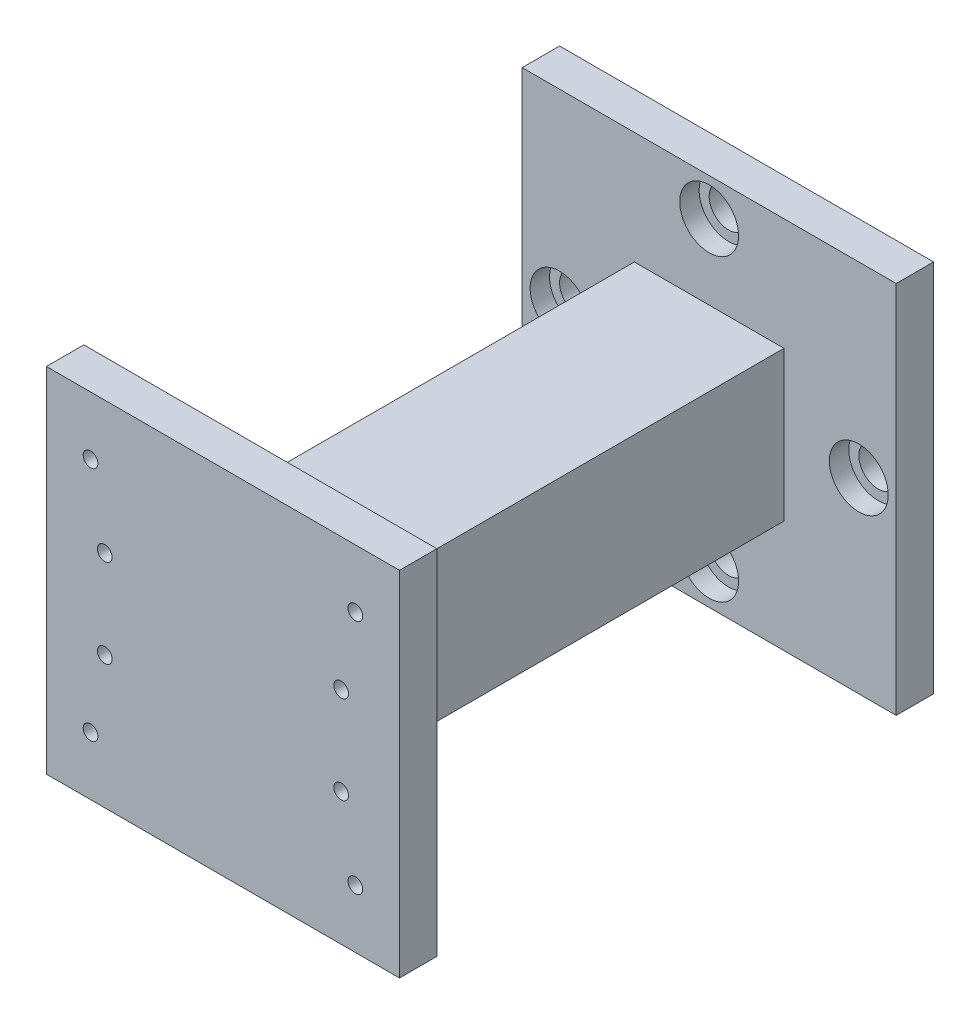
SolidWorks part; units mm, degrees
ref_plane "Front Plane" through (0, 0, 0) normal (0, 0, 1) x (1, 0, 0)
ref_plane "Top Plane" through (0, 0, 0) normal (0, 1, 0) x (1, 0, 0)
ref_plane "Right Plane" through (0, 0, 0) normal (1, 0, 0) x (0, 0, -1)
sketch "Sketch2" plane through (0, 0, 0) normal (0, 0, 1) x (1, 0, 0)
  line L0 (0, 0) -> (63.5, 0)
  line L1 (63.5, 0) -> (63.5, 63.5)
  line L2 (63.5, 63.5) -> (0, 63.5)
  line L3 (0, 63.5) -> (0, 0)
  dimension "D1" = 63.5
  dimension "D2" = 63.5
extrude "Boss-Extrude2" add sketch "Sketch2" along normal blind 6.35
sketch "Sketch3" plane through (0, 0, 6.35) normal (0, 0, 1) x (1, 0, 0)
  line L0 (19.05, 44.45) -> (19.05, 19.05)
  line L1 (19.05, 19.05) -> (44.45, 19.05)
  line L2 (44.45, 19.05) -> (44.45, 44.45)
  line L3 (44.45, 44.45) -> (19.05, 44.45)
  line L4 (0, 0) -> (63.5, 0) construction
  line L5 (63.5, 0) -> (63.5, 63.5) construction
  dimension "D1" = 25.4
  dimension "D2" = 25.4
  dimension "D3" = 19.05
  dimension "D4" = 19.05
extrude "Boss-Extrude3" add sketch "Sketch3" along normal blind 76.2
sketch "Sketch14" plane through (0, 0, 82.55) normal (0, 0, 1) x (1, 0, 0)
  line L0 (1.778, 61.722) -> (61.722, 61.722)
  line L1 (61.722, 61.722) -> (61.722, 1.778)
  line L2 (61.722, 1.778) -> (1.778, 1.778)
  line L3 (1.778, 1.778) -> (1.778, 61.722)
  line L4 (63.5, 63.5) -> (0, 63.5) construction
  line L5 (0, 63.5) -> (0, 0) construction
  dimension "D1" = 59.944
  dimension "D2" = 59.944
  dimension "D3" = 1.778
  dimension "D4" = 1.778
extrude "Boss-Extrude6" add sketch "Sketch14" along normal blind 6.35
hole_wizard "CBORE for M6 SBHCS2" positions "Sketch17" profile "Sketch16" counterbore size "M6" standard "ANSI Metric"
sketch "Sketch17" plane through (0, 0, 6.35) normal (0, 0, 1) x (1, 0, 0)
  line L0 (63.5, 63.5) -> (0, 63.5) construction
  line L1 (0, 63.5) -> (0, 0) construction
  line L2 (0, 0) -> (63.5, 0) construction
  line L3 (63.5, 0) -> (63.5, 63.5) construction
  point P0 (57.15, 31.75)
  point P2 (31.75, 6.35)
  point P4 (31.75, 57.15)
  point P6 (6.35, 31.75)
  dimension "D1" = 6.35
  dimension "D2" = 31.75
  dimension "D3" = 6.35
  dimension "D4" = 31.75
  dimension "D5" = 6.35
  dimension "D6" = 31.75
  dimension "D7" = 6.35
  dimension "D8" = 31.75
sketch "Sketch16" plane through (57.15, 31.75, 6.35) normal (1, 0, 0) x (0, -1, 0)
  line L0 (0, 0) -> (0, 9.6028)
  line L1 (0, 9.6028) -> (3.3, 7.62)
  line L2 (3.3, 7.62) -> (3.3, 3.3)
  line L3 (3.3, 3.3) -> (5, 3.3)
  line L4 (5, 3.3) -> (5, 0)
  line L5 (5, 0) -> (0, 0)
  line L10 (0, 9.6028) -> (-3.3, 7.62) construction
  line L11 (0, -6.35) -> (0, 107.95) construction
  dimension "Hole Dia." = 6.6
  dimension "Hole Depth" = 7.62
  dimension "C'Bore Dia." = 10
  dimension "C'Bore Depth" = 3.3
  dimension "Drill Angle" = 118
hole_wizard "Tap Drill for M3x0.5 Tap2" positions "Sketch18" profile "Sketch19" hole size "M3x0.5" standard "ANSI Metric"
sketch "Sketch18" plane through (0, 0, 88.9) normal (0, 0, 1) x (1, 0, 0)
  line L0 (61.722, 1.778) -> (61.722, 61.722) construction
  line L1 (1.778, 1.778) -> (61.722, 1.778) construction
  line L2 (1.778, 61.722) -> (1.778, 1.778) construction
  line L3 (61.722, 61.722) -> (1.778, 61.722) construction
  point P0 (9.271, 51.816)
  point P2 (9.271, 11.684)
  point P4 (54.229, 11.684)
  point P6 (54.229, 51.816)
  point P8 (11.684, 39.243)
  point P10 (11.684, 24.257)
  point P12 (51.816, 39.243)
  point P14 (51.816, 24.257)
  dimension "D1" = 7.493
  dimension "D2" = 9.906
  dimension "D3" = 7.493
  dimension "D4" = 9.906
  dimension "D5" = 7.493
  dimension "D6" = 9.906
  dimension "D7" = 7.493
  dimension "D8" = 9.906
  dimension "D9" = 9.906
  dimension "D10" = 22.479
  dimension "D11" = 9.906
  dimension "D12" = 22.479
  dimension "D13" = 9.906
  dimension "D14" = 22.479
  dimension "D15" = 9.906
  dimension "D16" = 22.479
sketch "Sketch19" plane through (9.271, 51.816, 88.9) normal (1, 0, 0) x (0, -1, 0)
  line L0 (0, 0) -> (0, 8.3711)
  line L1 (0, 8.3711) -> (1.25, 7.62)
  line L2 (1.25, 7.62) -> (1.25, 0)
  line L5 (1.25, 0) -> (0, 0)
  line L10 (0, 8.3711) -> (-1.25, 7.62) construction
  line L11 (0, -6.35) -> (0, 107.95) construction
  dimension "Hole Dia." = 2.5
  dimension "Hole Depth" = 7.62
  dimension "Drill Angle" = 118
